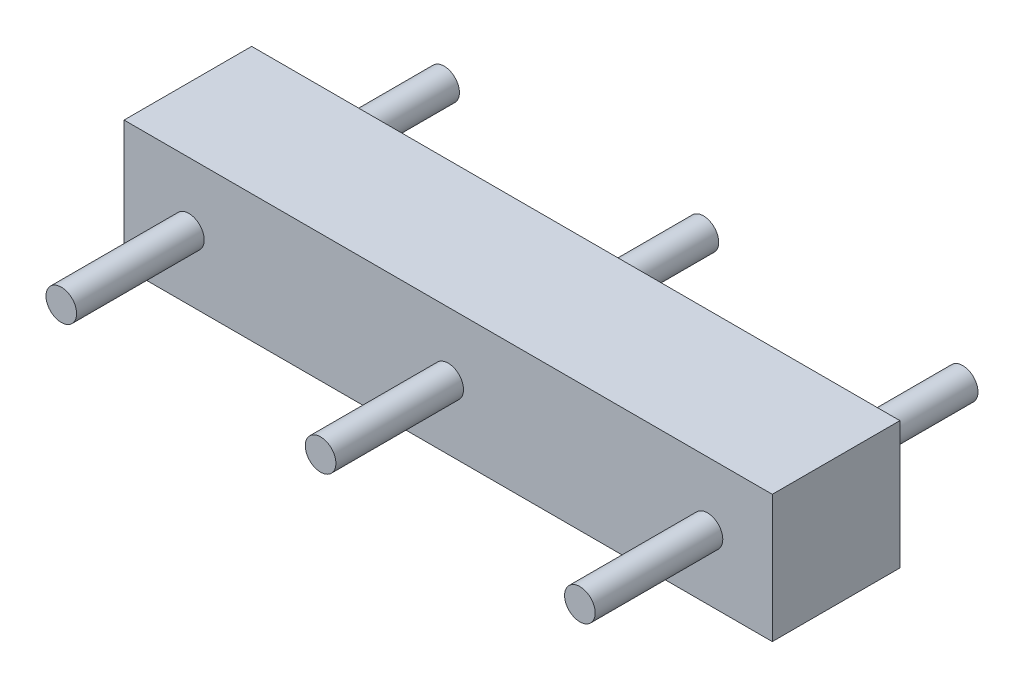
SolidWorks part; units mm, degrees
ref_plane "前视基准面" through (0, 0, 0) normal (0, 0, 1) x (1, 0, 0)
ref_plane "上视基准面" through (0, 0, 0) normal (0, 1, 0) x (1, 0, 0)
ref_plane "右视基准面" through (0, 0, 0) normal (1, 0, 0) x (0, 0, -1)
sketch "草图1" plane through (0, 0, 0) normal (0, 0, 1) x (1, 0, 0)
  line L1 (0, 0) -> (12.7, 0)
  line L2 (0, 0) -> (0, 2.5)
  line L3 (0, 2.5) -> (12.7, 2.5)
  line L4 (12.7, 0) -> (12.7, 2.5)
  dimension "D1" = 2.5
  dimension "D2" = 12.7
extrude "凸台-拉伸1" add sketch "草图1" along normal blind 2.5
sketch "草图2" plane through (0, 0, 2.5) normal (0, 0, 1) x (1, 0, 0)
  line L0 (6.35, 2.5) -> (6.35, -1.7995) construction
  line L1 (12.7, 2.5) -> (0, 2.5) construction
  line L2 (0, 1.25) -> (15.9024, 1.25) construction
  line L3 (0, 2.5) -> (0, 0) construction
  circle A0 centre (6.35, 1.25) radius 0.3
  dimension "D1" = 0
  dimension "D2" = 0.6
extrude "凸台-拉伸2" add sketch "草图2" along normal blind 2.5 and the other way blind 5
pattern_linear "阵列(线性)1" count 2 spacing 5.08 along (1, 0, 0) count 2 spacing 5.08 along (-1, 0, 0) of "凸台-拉伸2"
